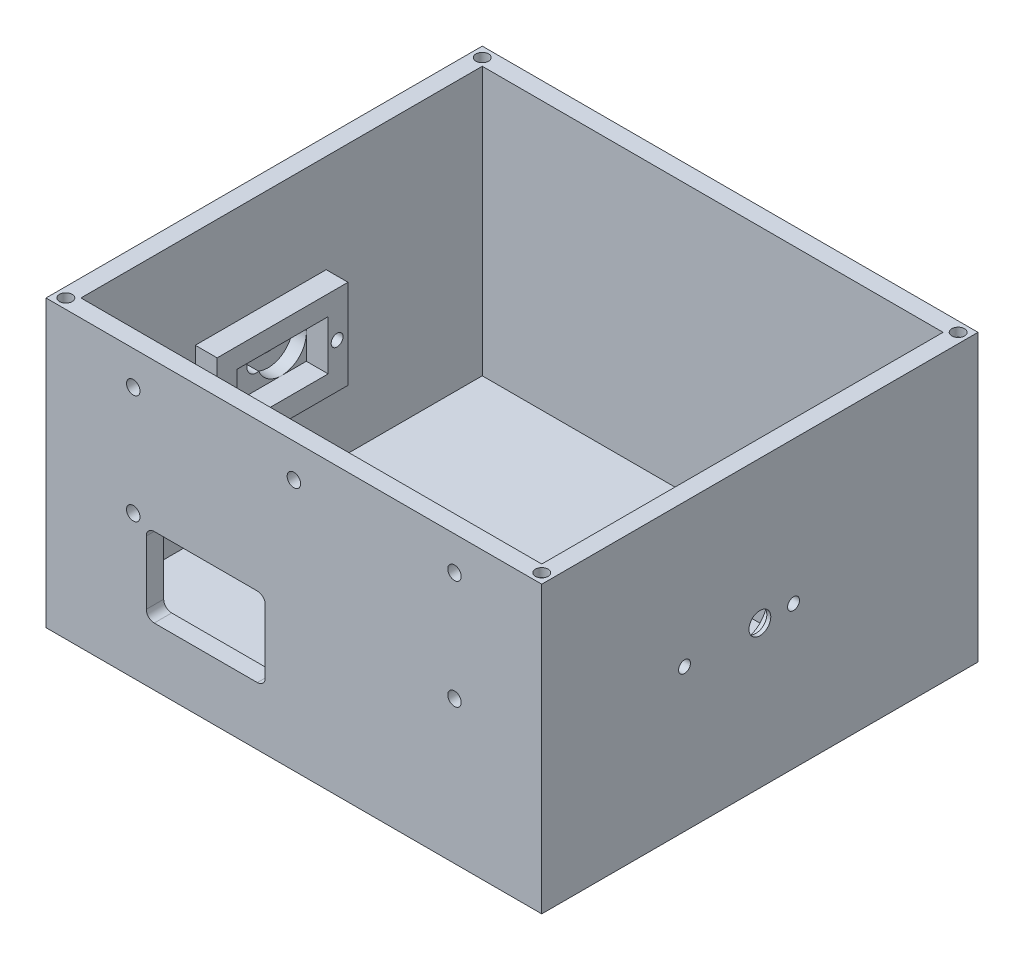
SolidWorks part; units mm, degrees
material "PE(聚乙烯)"
ref_plane "前视基准面" through (0, 0, 0) normal (0, 0, 1) x (1, 0, 0)
ref_plane "上视基准面" through (0, 0, 0) normal (0, 1, 0) x (1, 0, 0)
ref_plane "右视基准面" through (0, 0, 0) normal (1, 0, 0) x (0, 0, -1)
other "Configuration Table"
sketch "草图1" plane through (0, 0, 0) normal (0, 1, 0) x (1, 0, 0)
  line L1 (-62.5, 55) -> (62.5, 55)
  line L2 (-62.5, 55) -> (-62.5, -55)
  line L3 (-62.5, -55) -> (62.5, -55)
  line L4 (62.5, 55) -> (62.5, -55)
  line L5 (-62.5, 55) -> (62.5, -55) construction
  line L6 (-62.5, -55) -> (62.5, 55) construction
  point P0 (0, 0)
  dimension "D1" = 125
  dimension "D2" = 110
ref_plane "基准面1" through (0, 72, 0) normal (0, 1, 0) x (1, 0, 0)
sketch "草图2" plane through (0, 72, 0) normal (0, 1, 0) x (1, 0, 0)
  line L1 (-62.5, 55) -> (62.5, 55)
  line L2 (-62.5, 55) -> (-62.5, -55)
  line L3 (-62.5, -55) -> (62.5, -55)
  line L4 (62.5, 55) -> (62.5, -55)
  line L5 (-62.5, 55) -> (62.5, -55) construction
  line L6 (-62.5, -55) -> (62.5, 55) construction
  point P0 (0, 0)
  dimension "D1" = 125
  dimension "D2" = 110
loft "放样1" add profiles "草图1", "草图2"
shell "抽壳1" thickness 4.4
sketch "草图5" plane through (-62.5, 0, 0) normal (-1, 0, 0) x (0, 0, 1)
  arc A4 (5.75, 38.4495) -> (5.75, 33.5505) centre (0, 36) ccw
  arc A5 (5.75, 33.5505) -> (5.75, 38.4495) centre (6.25, 36) ccw
sketch "草图4" plane through (0, 0, 50.6) normal (0, 0, 1) x (1, 0, 0)
  line L0 (0, 0) -> (0, 47.53) construction
  line L1 (-22.2179, 24.6591) -> (82.9138, 24.6591) construction
  line L3 (-37.2179, 34.6591) -> (-7.2179, 34.6591)
  line L4 (-37.2179, 34.6591) -> (-37.2179, 14.6591)
  line L5 (-37.2179, 14.6591) -> (-7.2179, 14.6591)
  line L6 (-7.2179, 34.6591) -> (-7.2179, 14.6591)
  line L7 (-37.2179, 34.6591) -> (-7.2179, 14.6591) construction
  line L8 (-37.2179, 14.6591) -> (-7.2179, 34.6591) construction
  dimension "D1" = 30
  dimension "D2" = 20
extrude "切除-拉伸2" cut sketch "草图4" along normal through all
fillet "圆角1" radius 2 4 edges at (-7.2179, 34.6591, 52.8) (-7.2179, 14.6591, 52.8) (-37.2179, 14.6591, 52.8) (-37.2179, 34.6591, 52.8)
sketch "草图6" plane through (-58.1, 0, 0) normal (1, 0, 0) x (0, 0, -1)
  line L2 (-16.75, 29.75) -> (-16.75, 42.25) construction
  line L6 (6.25, 42.25) -> (6.25, 29.75) construction
  line L8 (-21.75, 42.25) -> (-21.75, 29.75) construction
  line L10 (-16.75, 29.75) -> (-16.75, 42.25) construction
  line L12 (11.25, 29.75) -> (11.25, 42.25) construction
  line L14 (6.25, 42.25) -> (6.25, 29.75) construction
  line L17 (-16.75, 42.25) -> (6.25, 42.25)
  line L18 (-21.75, 42.25) -> (-21.75, 47.25)
  line L19 (-21.75, 47.25) -> (11.25, 47.25)
  line L20 (11.25, 42.25) -> (11.25, 47.25)
  line L21 (-16.75, 29.75) -> (6.25, 29.75)
  line L22 (-21.75, 29.75) -> (-21.75, 24.75)
  line L23 (-21.75, 24.75) -> (11.25, 24.75)
  line L24 (11.25, 29.75) -> (11.25, 24.75)
  line L26 (-21.75, 42.25) -> (-21.75, 29.75)
  line L28 (-16.75, 42.25) -> (-16.75, 29.75)
  line L30 (6.25, 42.25) -> (6.25, 29.75)
  line L32 (11.25, 42.25) -> (11.25, 29.75)
  circle A0 centre (8.5, 36) radius 1.5 construction
  circle A1 centre (-19, 36) radius 1.5 construction
  circle A2 centre (8.5, 36) radius 1.5 construction
  circle A3 centre (-19, 36) radius 1.5 construction
  dimension "D1" = 5
  dimension "D2" = 5
  dimension "D3" = 5
  dimension "D4" = 5
extrude "凸台-拉伸1" add sketch "草图6" along normal blind 5.5
sketch "草图7" plane through (-52.6, 0, 0) normal (1, 0, 0) x (0, 0, -1)
  circle A0 centre (-19, 36) radius 1.5
  circle A1 centre (8.5, 36) radius 1.5
  dimension "D1" = 3
  dimension "D2" = 3
extrude "切除-拉伸3" cut sketch "草图7" against normal through all
mirror "镜向1" about plane through (0, 0, 0) normal (1, 0, 0) of "切除-拉伸3", "凸台-拉伸1"
sketch "草图8" plane through (0, 72, 0) normal (0, 1, 0) x (1, 0, 0)
  line L5 (-60, 52.5) -> (-60, -55)
  line L6 (62.5, 52.5) -> (-60, 52.5)
  line L7 (-60, 52.5) -> (-60, -52.5) construction
  line L8 (60, 52.5) -> (-60, 52.5) construction
  line L13 (-62.5, -52.5) -> (60, -52.5)
  line L14 (60, -52.5) -> (60, 55)
  line L15 (-60, -52.5) -> (60, -52.5) construction
  line L16 (60, -52.5) -> (60, 52.5) construction
  circle A0 centre (-60, 52.5) radius 1.6
  circle A1 centre (-60, -52.5) radius 1.6
  circle A2 centre (60, -52.5) radius 1.6
  circle A3 centre (60, 52.5) radius 1.6
  dimension "D3" = 3.2
  dimension "D2" = 2.5
  dimension "D1" = 2.5
extrude "切除-拉伸4" cut sketch "草图8" against normal blind 2.2
sketch "草图3" plane through (-58.1, 0, 0) normal (1, 0, 0) x (0, 0, -1)
  line L0 (0, 0) -> (0, 87.4654) construction
  line L1 (-55, 0) -> (55, 0) construction
  line L2 (55, 36) -> (-55, 36) construction
  line L3 (55, 0) -> (55, 72) construction
  line L4 (-55, 0) -> (-55, 72) construction
  arc A1 (-5.75, 38.4495) -> (-5.75, 33.5505) centre (-6.25, 36) ccw construction
  arc A2 (-5.75, 33.5505) -> (-5.75, 38.4495) centre (0, 36) ccw construction
  arc A3 (-5.75, 38.4495) -> (-5.75, 33.5505) centre (-6.25, 36) ccw
  arc A4 (-5.75, 33.5505) -> (-5.75, 38.4495) centre (0, 36) ccw
extrude "切除-拉伸1" cut sketch "草图3" against normal offset from surface (3.4 mm away) 1 up to face at (-62.5, 37.5, 19)
sketch "草图9" plane through (58.1, 0, 0) normal (-1, 0, 0) x (0, 0, 1)
  arc A2 (5.75, 38.4495) -> (5.75, 33.5505) centre (0, 36) ccw
  arc A3 (5.75, 33.5505) -> (5.75, 38.4495) centre (6.25, 36) ccw
  arc A4 (5.75, 38.4495) -> (5.75, 33.5505) centre (0, 36) ccw
  arc A5 (5.75, 33.5505) -> (5.75, 38.4495) centre (6.25, 36) ccw
  dimension "D1" = 0
extrude "切除-拉伸5" cut sketch "草图9" against normal offset from surface (3.4 mm away) 1 up to face at (62.5, 34.5, 19)
sketch "草图10" plane through (-61.5, 0, 0) normal (1, 0, 0) x (0, 0, -1)
  circle A0 centre (0, 36) radius 2.75
  dimension "D1" = 5.5
extrude "切除-拉伸6" cut sketch "草图10" against normal through all both and the other way through all
sketch "草图11" plane through (0, 0, -55) normal (0, 0, -1) x (-1, 0, 0)
  line L0 (34.5, 73) -> (34.5, -5.4747) construction
  line L1 (16.5, 73) -> (16.5, -5.4747) construction
  line L2 (42.5, 73) -> (42.5, -5.4747) construction
  line L3 (24.5, 73) -> (24.5, -5.4747) construction
  circle A0 centre (42.5, 24.5436) radius 3
  circle A1 centre (24.5, 24.5436) radius 3
  dimension "D3" = 6
  dimension "D1" = 8
  dimension "D2" = 8
extrude "凸台-拉伸2" add sketch "草图11" along normal blind 3
sketch "草图12" plane through (0, 0, 50.6) normal (0, 0, -1) x (-1, 0, 0)
  circle A10 centre (-40.5, 36) radius 1.5
  circle A11 centre (-40.5, 63.5) radius 1.5
  circle A12 centre (0, 63.5) radius 1.5
  circle A14 centre (40.5, 36) radius 1.5
  circle A15 centre (40.5, 63.5) radius 1.5
hole_wizard "M3 间隙孔1" positions "草图13" profile "草图14" hole size "M3" standard "GB"
sketch "草图13" plane through (0, 0, 50.6) normal (0, 0, -1) x (-1, 0, 0)
  point P0 (-40.5, 63.5)
  point P3 (0, 63.5)
  point P6 (40.5, 63.5)
  point P9 (40.5, 36)
  point P21 (-40.5, 36)
sketch "草图14" plane through (40.5, 63.5, 50.6) normal (1, 0, 0) x (0, 1, 0)
  line L0 (0, 0) -> (0, 4.4001)
  line L1 (0, 4.4001) -> (1.7, 4.4001)
  line L2 (1.7, 4.4001) -> (1.7, 0)
  line L5 (1.7, 0) -> (0, 0)
  line L11 (0, -6.35) -> (0, 107.95) construction
  dimension "通孔孔直径" = 3.4
  dimension "通孔孔深度" = 4.4001
sketch "草图15" plane through (0, 0, 50.6) normal (0, 0, -1) x (-1, 0, 0)
  line L0 (-29.1, 60) -> (-29.1, 58)
  line L1 (-29.1, 58) -> (-33.1, 58)
  line L2 (-4.8254, 58) -> (-4.8254, 60)
  line L3 (-0.8253, 58) -> (-4.8254, 58)
  line L4 (-4.8254, 32.0254) -> (-0.8253, 32.0254)
  line L5 (-4.8254, 30.0253) -> (-4.8254, 32.0254)
  line L6 (-29.1, 32.0254) -> (-29.1, 30.0253)
  line L7 (-33.1, 32.0254) -> (-29.1, 32.0254)
  line L8 (-33.1, 58) -> (-33.1, 57)
  line L9 (-33.1, 57) -> (-28.1127, 57)
  line L10 (-28.1127, 57) -> (-28.1, 60)
  line L11 (-28.1, 60) -> (-29.1, 60)
  line L12 (-5.8127, 33.0254) -> (-0.8253, 33.0254)
  line L13 (-0.8253, 33.0254) -> (-0.8253, 57)
  line L14 (-0.8253, 57) -> (-5.8127, 57)
  line L15 (-5.8254, 57.0127) -> (-5.8254, 60)
  line L16 (-5.8254, 60) -> (-28.1, 60)
  line L17 (-28.1, 60) -> (-28.1, 57.0127)
  line L18 (-28.1127, 57) -> (-33.1, 57)
  line L19 (-33.1, 57) -> (-33.1, 33.0254)
  line L20 (-33.1, 33.0254) -> (-28.1127, 33.0254)
  line L21 (-28.1, 33.0127) -> (-28.1, 30.0253)
  line L22 (-28.1, 30.0253) -> (-5.8254, 30.0253)
  line L23 (-5.8254, 30.0253) -> (-5.8254, 33.0127)
  line L24 (-5.8127, 33.0254) -> (-0.8253, 33.0254) construction
  line L25 (-0.8253, 33.0254) -> (-0.8253, 57) construction
  line L26 (-0.8253, 57) -> (-5.8127, 57) construction
  line L27 (-5.8254, 57.0127) -> (-5.8254, 60) construction
  line L28 (-5.8254, 60) -> (-28.1, 60) construction
  line L29 (-28.1, 60) -> (-28.1, 57.0127) construction
  line L30 (-28.1127, 57) -> (-33.1, 57) construction
  line L31 (-33.1, 57) -> (-33.1, 33.0254) construction
  line L32 (-33.1, 33.0254) -> (-28.1127, 33.0254) construction
  line L33 (-28.1, 33.0127) -> (-28.1, 30.0253) construction
  line L34 (-28.1, 30.0253) -> (-5.8254, 30.0253) construction
  line L35 (-5.8254, 30.0253) -> (-5.8254, 33.0127) construction
  line L36 (-0.8253, 57) -> (-5.8254, 57.0127)
  line L37 (-5.8254, 57.0127) -> (-5.8254, 60)
  line L38 (-5.8254, 60) -> (-4.8254, 60)
  line L39 (-0.8253, 33.0254) -> (-5.8254, 33.0127)
  line L40 (-5.8254, 33.0127) -> (-5.8254, 30.0253)
  line L41 (-5.8254, 30.0253) -> (-4.8254, 30.0253)
  line L42 (-0.8253, 32.0254) -> (-0.8253, 33.0254)
  line L43 (-0.8253, 58) -> (-0.8253, 57)
  line L45 (-28.1, 33.0127) -> (-28.1, 30.0253)
  line L46 (-28.1, 30.0253) -> (-29.1, 30.0253)
  line L47 (-33.1, 32.0254) -> (-33.1, 33.0254)
  line L48 (-29.1, 33.0127) -> (-29.1, 30.0253) construction
  line L49 (-33.1, 32.0254) -> (-28.1127, 32.0254) construction
  line L50 (-28.1, 33.0127) -> (-28.1, 33.0254)
  line L51 (-28.1, 33.0254) -> (-33.1, 33.0254)
  line L52 (-5.8127, 32.0254) -> (-0.8253, 32.0254) construction
  line L53 (-4.8254, 30.0253) -> (-4.8254, 33.0127) construction
  line L54 (-0.8253, 58) -> (-5.8127, 58) construction
  line L55 (-4.8254, 57.0127) -> (-4.8254, 60) construction
  line L56 (-28.1127, 58) -> (-33.1, 58) construction
  line L57 (-29.1, 60) -> (-29.1, 57.0127) construction
  arc A4 (-5.8254, 57.0127) -> (-5.8127, 57) centre (-5.8127, 57.0127) ccw
  arc A5 (-28.1127, 57) -> (-28.1, 57.0127) centre (-28.1127, 57.0127) ccw
  arc A6 (-28.1, 33.0127) -> (-28.1127, 33.0254) centre (-28.1127, 33.0127) ccw
  arc A7 (-5.8127, 33.0254) -> (-5.8254, 33.0127) centre (-5.8127, 33.0127) ccw
  arc A8 (-5.8254, 57.0127) -> (-5.8127, 57) centre (-5.8127, 57.0127) ccw construction
  arc A9 (-28.1127, 57) -> (-28.1, 57.0127) centre (-28.1127, 57.0127) ccw construction
  arc A10 (-28.1, 33.0127) -> (-28.1127, 33.0254) centre (-28.1127, 33.0127) ccw construction
  arc A11 (-5.8127, 33.0254) -> (-5.8254, 33.0127) centre (-5.8127, 33.0127) ccw construction
  dimension "D1" = 0
  dimension "D2" = 1
extrude "凸台-拉伸3" add sketch "草图15" along normal blind 3
